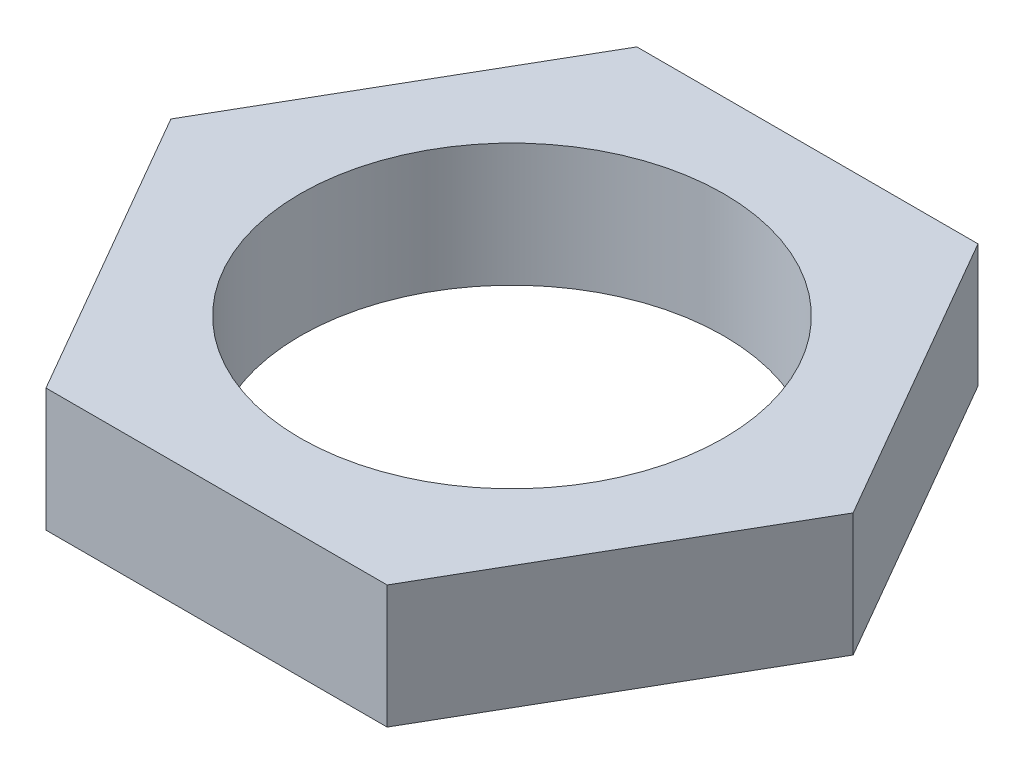
SolidWorks part; units mm, degrees
material "PE haute densité"
ref_plane "Plan de face" through (0, 0, 0) normal (0, 0, 1) x (1, 0, 0)
ref_plane "Plan de dessus" through (0, 0, 0) normal (0, 1, 0) x (1, 0, 0)
ref_plane "Plan de droite" through (0, 0, 0) normal (1, 0, 0) x (0, 0, -1)
sketch "Esquisse1" plane through (0, 0, 0) normal (0, 1, 0) x (1, 0, 0)
  line L1 (6.9282, -12) -> (13.8564, 0)
  line L2 (13.8564, 0) -> (6.9282, 12)
  line L3 (6.9282, 12) -> (-6.9282, 12)
  line L4 (-6.9282, 12) -> (-13.8564, 0)
  line L5 (-13.8564, 0) -> (-6.9282, -12)
  line L6 (-6.9282, -12) -> (6.9282, -12)
  circle A0 centre (0, 0) radius 12 construction
  circle A1 centre (0, 0) radius 8.6
  dimension "D2" = 17.2
  dimension "D1" = 24
extrude "Extrusion1" add sketch "Esquisse1" along normal blind 5
